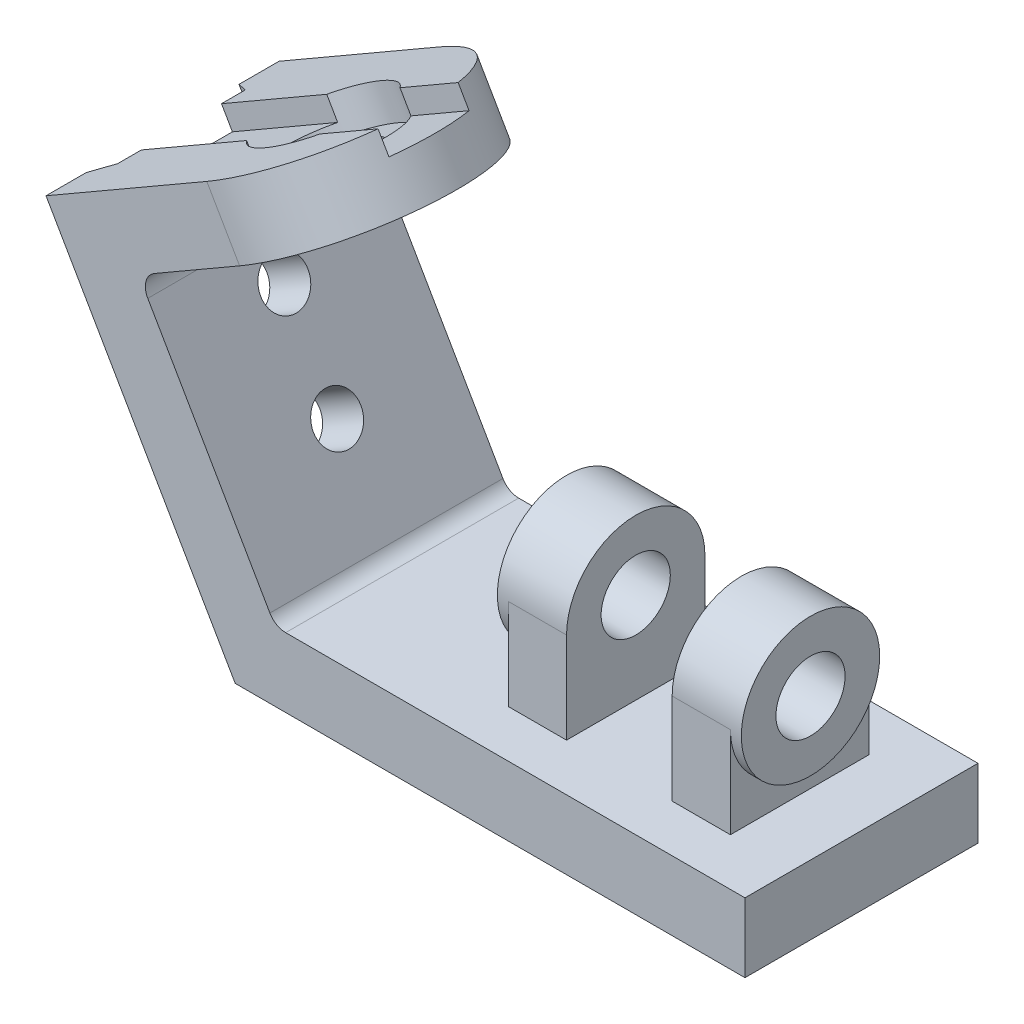
SolidWorks part; units mm, degrees
ref_plane "Front Plane" through (0, 0, 0) normal (0, 0, 1) x (1, 0, 0)
ref_plane "Top Plane" through (0, 0, 0) normal (0, 1, 0) x (1, 0, 0)
ref_plane "Right Plane" through (0, 0, 0) normal (1, 0, 0) x (0, 0, -1)
sketch "Croquis1" plane through (0, 0, 0) normal (0, 1, 0) x (1, 0, 0)
  line L1 (70, -32) -> (-70, -32)
  line L2 (70, -32) -> (70, 32)
  line L3 (70, 32) -> (-70, 32)
  line L4 (-70, -32) -> (-70, 32)
  line L5 (70, -32) -> (-70, 32) construction
  line L6 (70, 32) -> (-70, -32) construction
  point P0 (0, 0)
  dimension "D1" = 64
  dimension "D2" = 140
extrude "Saliente-Extruir1" add sketch "Croquis1" along normal blind 19
ref_plane "Plano1" through (37, 0, 0) normal (1, 0, 0) x (0, 0, -1)
sketch "Croquis2" plane through (37, 0, 0) normal (1, 0, 0) x (0, 0, -1)
  line L0 (-32, 19) -> (32, 19) construction
  circle A0 centre (0, 44) radius 19
  circle A1 centre (0, 44) radius 9.5
  dimension "D1" = 38
  dimension "D2" = 19
  dimension "D3" = 25
extrude "Saliente-Extruir2" add sketch "Croquis2" along normal blind 19 separate body
sketch "Croquis4" plane through (37, 0, 0) normal (1, 0, 0) x (0, 0, -1)
  line L0 (-32, 19) -> (32, 19) construction
  line L2 (-19, 44) -> (-19, 19)
  line L3 (-19, 19) -> (19, 19)
  line L4 (19, 44) -> (19, 19)
  circle A0 centre (0, 44) radius 19 construction
  circle A1 centre (0, 44) radius 19 construction
  circle A2 centre (0, 44) radius 19
extrude "Saliente-Extruir3" add sketch "Croquis4" along normal blind 16 contours A2 L2 L3 L4
ref_plane "Plano2" through (8, 0, 0) normal (1, 0, 0) x (0, 0, -1)
sketch "Croquis5" plane through (8, 0, 0) normal (1, 0, 0) x (0, 0, -1)
  circle A0 centre (0, 44) radius 9.5 construction
  circle A1 centre (0, 44) radius 19 construction
  circle A2 centre (0, 44) radius 9.5
  circle A3 centre (0, 44) radius 19
extrude "Saliente-Extruir4" add sketch "Croquis5" against normal blind 19 separate body
sketch "Croquis6" plane through (8, 0, 0) normal (1, 0, 0) x (0, 0, -1)
  line L0 (19, 44) -> (19, 19) construction
  line L1 (-19, 19) -> (19, 19) construction
  line L2 (-19, 44) -> (-19, 19) construction
  line L3 (19, 44) -> (19, 19)
  line L4 (-19, 19) -> (19, 19)
  line L5 (-19, 44) -> (-19, 19)
  circle A0 centre (0, 44) radius 19 construction
  circle A1 centre (0, 44) radius 19
extrude "Saliente-Extruir5" add sketch "Croquis6" against normal blind 16 contours A1 L5 L4 L3
sketch "Croquis7" plane through (0, 0, 32) normal (0, 0, 1) x (1, 0, 0)
  line L0 (-70, 0) -> (-82.9453, 0) construction
  line L1 (-70, 0) -> (-121.9615, 90)
  line L2 (-121.9615, 90) -> (-105.507, 99.5)
  line L3 (-105.507, 99.5) -> (-59.0303, 19)
  line L4 (-70, 19) -> (70, 19) construction
  line L5 (-70, 0) -> (-70, 19)
  line L6 (-70, 19) -> (-59.0303, 19)
  dimension "D1" = 60
  dimension "D2" = 90
  dimension "D3" = 19
extrude "Saliente-Extruir6" add sketch "Croquis7" against normal blind 64
sketch "Croquis9" plane through (-69.4615, 120.3109, 0) normal (-0.5, 0.866, 0) x (0.866, 0.5, 0)
  line L1 (-60.6218, 32) -> (-9.6218, 32)
  line L2 (-60.6218, 32) -> (-60.6218, -32)
  line L3 (-60.6218, -32) -> (-9.6218, -32)
  arc A0 (-9.6218, -32) -> (-9.6218, 32) centre (-9.6218, 0) ccw
  point P6 (0, 0)
  dimension "D1" = 51
extrude "Saliente-Extruir9" add sketch "Croquis9" against normal blind 18 contours A0 L1 L2 L3
sketch "Croquis14" plane through (-69.4615, 120.3109, 0) normal (-0.5, 0.866, 0) x (0.866, 0.5, 0)
  circle A0 centre (-9.6218, 0) radius 16
  dimension "D1" = 32
extrude "Cortar-Extruir1" cut sketch "Croquis14" against normal blind 9
sketch "Croquis16" plane through (-69.4615, 120.3109, 0) normal (-0.5, 0.866, 0) x (0.866, 0.5, 0)
  circle A0 centre (-9.6218, 0) radius 9.5
  dimension "D1" = 19
extrude "Cortar-Extruir2" cut sketch "Croquis16" against normal blind 19
sketch "Croquis17" plane through (-69.4615, 120.3109, 0) normal (-0.5, 0.866, 0) x (0.866, 0.5, 0)
  line L0 (-60.6218, 0) -> (22.3782, 0) construction
  line L1 (-60.6218, 32) -> (-60.6218, -32) construction
  line L2 (-60.6218, -11) -> (20.4282, -11)
  line L3 (-60.6218, 11) -> (20.4282, 11)
  line L4 (-60.6218, 11) -> (-60.6218, -11)
  line L5 (-60.6218, -11) -> (22.3782, -11) construction
  line L6 (-60.6218, 11) -> (22.3782, 11) construction
  arc A0 (-9.6218, -32) -> (-9.6218, 32) centre (-9.6218, 0) ccw construction
  arc A1 (20.4282, -11) -> (20.4282, 11) centre (-9.6218, 0) ccw
  point P5 (22.3782, 0)
  point P15 (-60.6218, -11)
  point P17 (-60.6218, 11)
  dimension "D1" = 11
  dimension "D2" = 11
extrude "Cortar-Extruir3" cut sketch "Croquis17" against normal blind 6
sketch "Croquis18" plane through (-69.4615, 120.3109, 0) normal (-0.5, 0.866, 0) x (0.866, 0.5, 0)
  line L0 (-60.6218, 21) -> (-50.9556, 21) construction
  line L1 (-60.6218, 32) -> (-60.6218, 11) construction
  line L2 (-60.6218, 21) -> (-54.6218, 17.5359)
  line L3 (-54.6218, 17.5359) -> (-54.6218, -17.5359)
  line L4 (-54.6218, 0) -> (-63.9133, 0) construction
  line L5 (-60.6218, -21) -> (-54.6218, -17.5359)
  line L6 (-60.6218, 21) -> (-60.6218, -21)
  dimension "D1" = 30
  dimension "D2" = 6
  dimension "D3" = 11
extrude "Cortar-Extruir4" cut sketch "Croquis18" against normal through all
sketch "Croquis19" plane through (-47.3038, -27.3109, 0) normal (-0.866, -0.5, 0) x (0, 0, 1)
  line L0 (11, 132.923) -> (-11, 132.923) construction
  circle A0 centre (0, 104.923) radius 6.5
  circle A1 centre (0, 75.923) radius 6.5
  dimension "D3" = 13
  dimension "D4" = 13
  dimension "D1" = 28
  dimension "D2" = 29
extrude "Cortar-Extruir5" cut sketch "Croquis19" against normal through all
fillet "Redondeo1" radius 5 2 edges at (-59.0303, 19, 0) (-96.507, 83.9115, 0)
